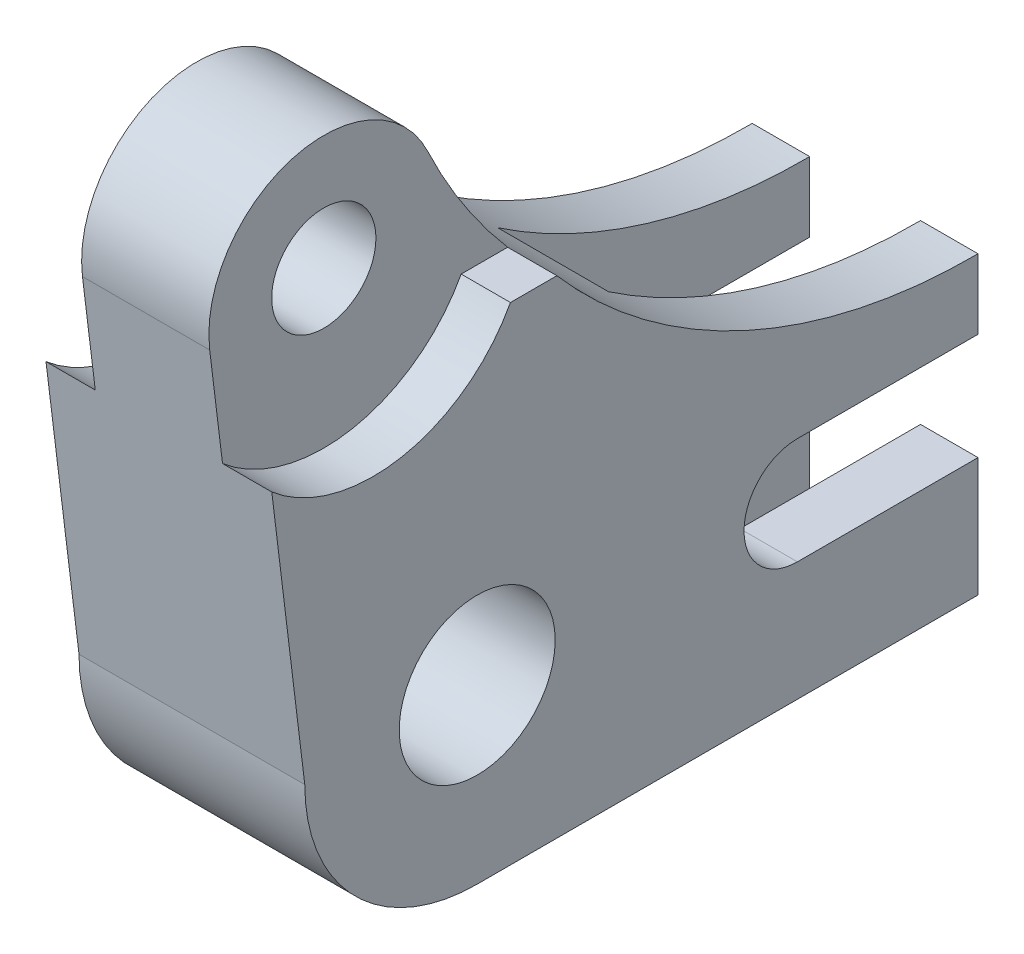
SolidWorks part; units mm, degrees
material "AISI 1020"
ref_plane "Front Plane" through (0, 0, 0) normal (0, 0, 1) x (1, 0, 0)
ref_plane "Top Plane" through (0, 0, 0) normal (0, 1, 0) x (1, 0, 0)
ref_plane "Right Plane" through (0, 0, 0) normal (1, 0, 0) x (0, 0, -1)
sketch "Sketch1" plane through (0, 0, 0) normal (1, 0, 0) x (0, 0, -1)
  line L0 (0, 65.8737) -> (0, 0) construction
  line L1 (0, 0) -> (70.9292, 0) construction
  line L2 (0, 0) -> (-17.9439, 66.9677) construction
  line L3 (39, 6.5) -> (61, 6.5)
  line L4 (39, -6.5) -> (61, -6.5)
  line L5 (39, 6.5) -> (39, -6.5) construction
  line L6 (0, -21) -> (61, -21)
  line L7 (-26.5787, 45.6314) -> (-21, 0)
  line L8 (61, 6.5) -> (61, 15)
  line L9 (61, -6.5) -> (61, -21)
  line L11 (61.0928, -14.5215) -> (61.0928, 176.0632) construction
  line L12 (-25.1442, 80.7708) -> (119.9484, 80.7708) construction
  circle A0 centre (0, 0) radius 9.5
  circle A1 centre (-12.6821, 47.3304) radius 6.35
  arc A2 (39, 6.5) -> (39, -6.5) centre (39, 0) ccw
  arc A3 (-0.0292, 53.3224) -> (-26.5787, 45.6314) centre (-12.6821, 47.3304) ccw
  arc A4 (-21, 0) -> (0, -21) centre (0, 0) ccw
  arc A6 (-0.0292, 53.3224) -> (61, 15) centre (60.524, 81.9983) ccw
  dimension "D2" = 19
  dimension "D3" = 12.7
  dimension "D5" = 13
  dimension "D7" = 28
  dimension "D8" = 42
  dimension "D10" = 67
  dimension "D11" = 61
  dimension "D1" = 15
  dimension "D4" = 49
  dimension "D6" = 22
  dimension "D9" = 36
  dimension "D12" = 21
extrude "Boss-Extrude1" add sketch "Sketch1" along normal blind 27.5
sketch "Sketch4" plane through (0, 0, 0) normal (-1, 0, 0) x (0, 0, 1)
  line L0 (26.5787, 45.6314) -> (21, 0) construction
  line L1 (-9.7095, 38.3304) -> (-4.0511, 38.3304)
  line L2 (12.6821, 47.3304) -> (-8.3433, 47.3304) construction
  arc A0 (25.0199, 32.8811) -> (-4.0511, 38.3304) centre (12.6821, 47.3304) cw
  arc A1 (-61, 15) -> (0.0292, 53.3224) centre (-60.524, 81.9983) ccw construction
  dimension "D1" = 19
  dimension "D2" = 9
extrude "Cut-Extrude2" cut sketch "Sketch4" against normal blind 6 and the other way through all
sketch "Sketch6" plane through (27.5, 0, 0) normal (1, 0, 0) x (0, 0, -1)
  line L0 (-26.5787, 45.6314) -> (-21, 0) construction
  line L1 (-24.4407, 47.3304) -> (18.6984, 47.3304) construction
  line L2 (4.0511, 38.3304) -> (9.7095, 38.3304)
  arc A0 (-25.0199, 32.8811) -> (4.0511, 38.3304) centre (-12.6821, 47.3304) ccw
  arc A1 (-0.0292, 53.3224) -> (61, 15) centre (60.524, 81.9983) ccw construction
  dimension "D1" = 19
  dimension "D2" = 9
extrude "Cut-Extrude3" cut sketch "Sketch6" against normal blind 6 and the other way through all
sketch "Sketch7" plane through (27.5, 0, 0) normal (1, 0, 0) x (0, 0, -1)
  line L9 (9.7095, 38.3304) -> (4.0511, 38.3304)
  line L10 (-25.0199, 32.8811) -> (-21, 0)
  line L11 (0, -21) -> (61, -21)
  line L12 (61, -21) -> (61, -6.5)
  line L13 (61, -6.5) -> (39, -6.5)
  line L14 (39, 6.5) -> (61, 6.5)
  line L15 (61, 6.5) -> (61, 15)
  line L16 (9.7095, 38.3304) -> (4.0511, 38.3304)
  line L17 (-25.0199, 32.8811) -> (-21, 0)
  line L18 (0, -21) -> (61, -21)
  line L19 (61, -21) -> (61, -6.5)
  line L20 (61, -6.5) -> (39, -6.5)
  line L21 (39, 6.5) -> (61, 6.5)
  line L22 (61, 6.5) -> (61, 15)
  arc A5 (9.7095, 38.3304) -> (61, 15) centre (60.524, 81.9983) ccw
  arc A6 (-25.0199, 32.8811) -> (4.0511, 38.3304) centre (-12.6821, 47.3304) ccw
  arc A7 (-21, 0) -> (0, -21) centre (0, 0) ccw
  arc A8 (39, 6.5) -> (39, -6.5) centre (39, 0) ccw
  arc A9 (9.7095, 38.3304) -> (61, 15) centre (60.524, 81.9983) ccw
  arc A10 (-25.0199, 32.8811) -> (4.0511, 38.3304) centre (-12.6821, 47.3304) ccw
  arc A11 (-21, 0) -> (0, -21) centre (0, 0) ccw
  arc A12 (39, 6.5) -> (39, -6.5) centre (39, 0) ccw
  dimension "D2" = 0
ref_plane "Plane1" through (13.75, 0, 0) normal (1, 0, 0) x (0, 0, -1)
sketch "Sketch12" plane through (13.75, 0, 0) normal (1, 0, 0) x (0, 0, -1)
  line L0 (23, 26.492) -> (23, -21)
  line L1 (0, -21) -> (61, -21) construction
  line L9 (9.7095, 38.3304) -> (4.0511, 38.3304)
  line L10 (-25.0199, 32.8811) -> (-21, 0)
  line L11 (0, -21) -> (61, -21)
  line L12 (61, -21) -> (61, -6.5)
  line L13 (61, -6.5) -> (39, -6.5)
  line L14 (39, 6.5) -> (61, 6.5)
  line L15 (61, 6.5) -> (61, 15)
  line L16 (9.7095, 38.3304) -> (4.0511, 38.3304)
  line L17 (-25.0199, 32.8811) -> (-21, 0)
  line L18 (0, -21) -> (61, -21)
  line L19 (61, -21) -> (61, -6.5)
  line L20 (61, -6.5) -> (39, -6.5)
  line L21 (39, 6.5) -> (61, 6.5)
  line L22 (61, 6.5) -> (61, 15)
  arc A0 (9.7095, 38.3304) -> (61, 15) centre (60.524, 81.9983) ccw construction
  arc A5 (9.7095, 38.3304) -> (61, 15) centre (60.524, 81.9983) ccw
  arc A6 (-25.0199, 32.8811) -> (4.0511, 38.3304) centre (-12.6821, 47.3304) ccw
  arc A7 (-21, 0) -> (0, -21) centre (0, 0) ccw
  arc A8 (39, 6.5) -> (39, -6.5) centre (39, 0) ccw
  arc A9 (9.7095, 38.3304) -> (61, 15) centre (60.524, 81.9983) ccw
  arc A10 (-25.0199, 32.8811) -> (4.0511, 38.3304) centre (-12.6821, 47.3304) ccw
  arc A11 (-21, 0) -> (0, -21) centre (0, 0) ccw
  arc A12 (39, 6.5) -> (39, -6.5) centre (39, 0) ccw
  dimension "D1" = 38
  dimension "D2" = 0
extrude "Cut-Extrude5" cut sketch "Sketch12" against normal blind 6.75 and the other way blind 6.75 contours A12 L21 L22 A9 L0 L18 L19 L20
sketch "Sketch13" plane through (27.5, 0, 0) normal (1, 0, 0) x (0, 0, -1)
